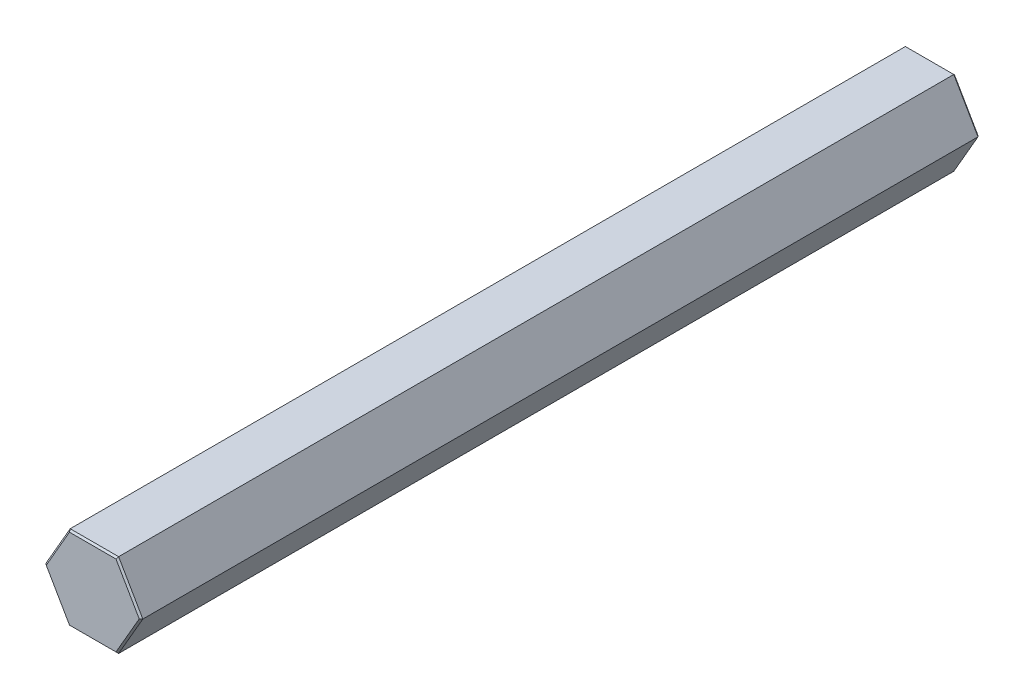
SolidWorks part; units mm, degrees
ref_plane "Front Plane" through (0, 0, 0) normal (0, 0, 1) x (1, 0, 0)
ref_plane "Top Plane" through (0, 0, 0) normal (0, 1, 0) x (1, 0, 0)
ref_plane "Right Plane" through (0, 0, 0) normal (1, 0, 0) x (0, 0, -1)
ref_plane "Plane1" through (0, 0, 0) normal (0, 0, -1) x (-1, 0, 0)
sketch "Sketch1" plane through (0, 0, 0) normal (0, 0, -1) x (-1, 0, 0)
  line L0 (3.6662, 6.35) -> (-3.6662, 6.35)
  line L1 (-3.6662, 6.35) -> (-7.3323, 0)
  line L2 (-7.3323, 0) -> (-3.6662, -6.35)
  line L3 (-3.6662, -6.35) -> (3.6662, -6.35)
  line L4 (3.6662, -6.35) -> (7.3323, 0)
  line L5 (7.3323, 0) -> (3.6662, 6.35)
extrude "Boss-Extrude1" add sketch "Sketch1" against normal blind 127
chamfer "Chamfer1" distance 0.254 angle 45 12 edges at (0, -6.35, 0) (5.4993, -3.175, 0) (-5.4993, -3.175, 0) (5.4993, 3.175, 0) (-5.4993, 3.175, 0) (0, 6.35, 0) (-5.4993, -3.175, 127) (0, -6.35, 127) (-5.4993, 3.175, 127) (5.4993, -3.175, 127) (0, 6.35, 127) (5.4993, 3.175, 127)
